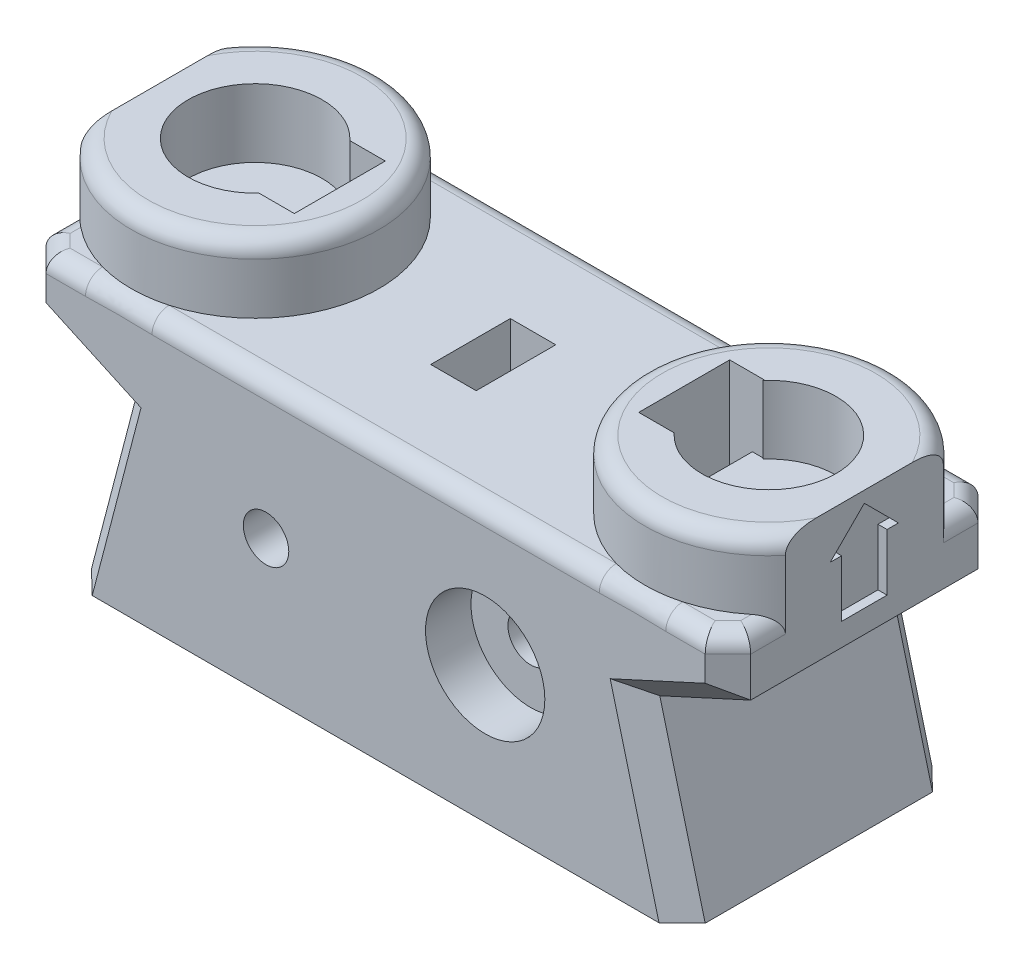
SolidWorks part; units mm, degrees
ref_plane "Front Plane" through (0, 0, 0) normal (0, 0, 1) x (1, 0, 0)
ref_plane "Top Plane" through (0, 0, 0) normal (0, 1, 0) x (1, 0, 0)
ref_plane "Right Plane" through (0, 0, 0) normal (1, 0, 0) x (0, 0, -1)
sketch "Sketch1" plane through (0, 0, 0) normal (0, 0, 1) x (1, 0, 0)
  line L1 (-15.5, 7.5) -> (15.5, 7.5)
  line L2 (-15.5, 7.5) -> (-15.5, -7.5)
  line L3 (-15.5, -7.5) -> (15.5, -7.5)
  line L4 (15.5, 7.5) -> (15.5, -7.5)
  line L5 (-15.5, 7.5) -> (15.5, -7.5) construction
  line L6 (-15.5, -7.5) -> (15.5, 7.5) construction
  point P0 (0, 0)
  dimension "D1" = 31
  dimension "D2" = 15
extrude "Boss-Extrude1" add sketch "Sketch1" along normal mid plane 12
sketch "Sketch2" plane through (0, -7.5, 0) normal (0, -1, 0) x (1, 0, 0)
  line L1 (-10.075, 3.075) -> (10.075, 3.075)
  line L2 (-10.075, 3.075) -> (-10.075, -3.075)
  line L3 (-10.075, -3.075) -> (10.075, -3.075)
  line L4 (10.075, 3.075) -> (10.075, -3.075)
  line L5 (-10.075, 3.075) -> (10.075, -3.075) construction
  line L6 (-10.075, -3.075) -> (10.075, 3.075) construction
  point P0 (0, 0)
  dimension "D1" = 20.15
  dimension "D2" = 6.15
extrude "Cut-Extrude1" cut sketch "Sketch2" against normal blind 13
sketch "Sketch3" plane through (0, 5.5, 0) normal (0, -1, 0) x (1, 0, 0)
  line L0 (8.075, 2.4473) -> (8.075, -2.8954) construction
  line L1 (7.575, 2) -> (8.575, 2)
  line L2 (7.575, 2) -> (7.575, -2)
  line L3 (7.575, -2) -> (8.575, -2)
  line L4 (8.575, 2) -> (8.575, -2)
  line L5 (10.075, -3.075) -> (10.075, 3.075) construction
  line L6 (-19.0138, 0) -> (22.2819, 0) construction
  line L7 (0, 7.5855) -> (0, -7.6677) construction
  line L8 (-8.575, 2) -> (-8.575, -2)
  line L9 (-7.575, -2) -> (-8.575, -2)
  line L10 (-7.575, 2) -> (-7.575, -2)
  line L11 (-7.575, 2) -> (-8.575, 2)
  line L12 (-0.825, 2.2727) -> (-0.825, -2.3089) construction
  line L17 (-10.075, 3.075) -> (-10.075, -3.075) construction
  line L19 (-1.825, 1.75) -> (0.175, 1.75)
  line L20 (-1.825, 1.75) -> (-1.825, -1.75)
  line L21 (-1.825, -1.75) -> (0.175, -1.75)
  line L22 (0.175, 1.75) -> (0.175, -1.75)
  dimension "D1" = 2
  dimension "D2" = 4
  dimension "D3" = 1
  dimension "D4" = 9.25
  dimension "D7" = 2
sketch "Sketch6" plane through (0, 7.5, 0) normal (0, 1, 0) x (1, 0, 0)
  line L0 (15.5, -6) -> (15.5, 6) construction
  line L1 (-15.5, -6) -> (-15.5, 6) construction
  line L2 (-17.2982, 0) -> (18.5048, 0) construction
  circle A0 centre (11.3, 0) radius 2.95
  circle A1 centre (-11.3, 0) radius 2.95
  circle A2 centre (-11.3, 0) radius 5.45
  circle A3 centre (11.3, 0) radius 5.45
  dimension "D1" = 5.9
  dimension "D3" = 5.9
  dimension "D5" = 2.5
  dimension "D6" = 2.5
  dimension "D2" = 4.2
  dimension "D4" = 4.2
extrude "Boss-Extrude3" add sketch "Sketch6" along normal blind 3
extrude "Cut-Extrude3" cut sketch "Sketch3" against normal up to surface (5 mm away) up to face at (-11.3, 10.5, 5.45)
sketch "Sketch7" plane through (0, 10.5, 0) normal (0, 1, 0) x (1, 0, 0)
  line L0 (-8.575, 2) -> (-9.1432, 2)
  line L1 (-9.1432, 2) -> (-9.1432, 0.6994)
  line L2 (-9.1432, 0.6994) -> (-8.575, 0.6994)
  line L3 (-8.575, -1.13) -> (-8.575, 1.13) construction
  line L4 (-8.575, 0.6994) -> (-8.575, 2)
  line L5 (-8.575, -1.13) -> (-8.575, -2)
  line L6 (-8.575, -2) -> (-9.1432, -2)
  line L7 (-9.1432, -2) -> (-9.1432, -0.71)
  line L8 (-9.1432, -0.71) -> (-8.575, -0.71)
  line L9 (-8.575, -0.71) -> (-8.575, -2)
  line L10 (8.575, 1.13) -> (8.575, 2)
  line L11 (8.575, 2) -> (9.0869, 2)
  line L12 (9.0869, 2) -> (9.0869, 1.13)
  line L13 (9.0869, 1.13) -> (8.575, 1.13)
  line L14 (8.575, -2) -> (8.575, -0.592)
  line L15 (8.575, 1.13) -> (8.575, -1.13) construction
  line L16 (8.575, -0.592) -> (9.4303, -0.592)
  line L17 (9.4303, -0.592) -> (9.4303, -2)
  line L18 (9.4303, -2) -> (8.575, -2)
  line M1 (-8.575, 1.13) -> (-8.575, 2)
  line M5 (-8.575, -2) -> (-8.575, -1.13)
  arc M6 (-8.575, -1.13) -> (-8.575, 1.13) centre (-11.3, 0) cw
extrude "Cut-Extrude4" cut sketch "Sketch7" against normal up to surface (3 mm away) contours L2 L4 L0 L1 M6 | L0 M1 M6 | L6 M5 M6 | L9 L8 L7 L6 M6 | L13 L12 L11 L10 | L18 L17 L16 L14 up to face at (11.4125, 7.5, 0)
sketch "Sketch8" plane through (0, -7.5, 0) normal (0, -1, 0) x (1, 0, 0)
  line L4 (-15.5, -6) -> (15.5, -6)
  line L5 (15.5, -6) -> (15.5, 6)
  line L6 (15.5, 6) -> (-15.5, 6)
  line L7 (-15.5, 6) -> (-15.5, -6)
  line L8 (-15.5, -6) -> (15.5, -6)
  line L9 (15.5, -6) -> (15.5, 6)
  line L10 (15.5, 6) -> (-15.5, 6)
  line L11 (-15.5, 6) -> (-15.5, -6)
  dimension "D1" = 0
extrude "Cut-Extrude5" cut sketch "Sketch8" against normal blind 3
sketch "Sketch9" plane through (0, 0, 6) normal (0, 0, 1) x (1, 0, 0)
  line L0 (10.07, -6.4416) -> (10.07, 14.1448) construction
  line L1 (-10.07, 14.1448) -> (-10.07, -6.4416) construction
  line L2 (-15.5, 7.5) -> (-15.5, -4.5) construction
  line L3 (15.5, -4.5) -> (15.5, 7.5) construction
  line L4 (5.82, 4.0391) -> (5.82, 0.7356) construction
  line L5 (-5.82, 4.8454) -> (-5.82, 0.9453) construction
  line L6 (-22.3049, 1.5) -> (21.0526, 1.5) construction
  line L7 (15.5, -4.5) -> (-15.5, -4.5) construction
  circle A0 centre (4.82, 1.5) radius 1
  circle A1 centre (-4.82, 1.5) radius 1
  point P14 (10.07, 3.8516)
  dimension "D3" = 2
  dimension "D4" = 2
  dimension "D1" = 5.43
  dimension "D2" = 5.43
  dimension "D5" = 4.25
  dimension "D6" = 4.25
  dimension "D7" = 6
extrude "Cut-Extrude6" cut sketch "Sketch9" against normal up to surface (12 mm away) up to face at (0, 1.5, -6)
sketch "Sketch10" plane through (0, 0, 6) normal (0, 0, 1) x (1, 0, 0)
  circle A0 centre (4.82, 1.5) radius 2.625
  dimension "D1" = 5.25
extrude "Cut-Extrude7" cut sketch "Sketch10" against normal blind 2
sketch "Sketch11" plane through (0, 0, -6) normal (0, 0, -1) x (-1, 0, 0)
  circle A0 centre (4.82, 1.5) radius 2.625
  dimension "D1" = 5.25
extrude "Cut-Extrude8" cut sketch "Sketch11" against normal blind 2
sketch "Sketch12" plane through (0, -4.5, 0) normal (0, -1, 0) x (1, 0, 0)
  line L0 (15.5, 3.4731) -> (15.5, -3.4731) construction
  line L1 (-15.5, -3.4731) -> (-15.5, 3.4731) construction
  line L2 (15.5, 3.4731) -> (15.5, -3.4731)
  line L3 (-15.5, -3.4731) -> (-15.5, 3.4731)
  arc A0 (15.5, -3.4731) -> (15.5, 3.4731) centre (11.3, 0) ccw construction
  arc A1 (-15.5, 3.4731) -> (-15.5, -3.4731) centre (-11.3, 0) ccw construction
  arc A2 (15.5, -3.4731) -> (15.5, 3.4731) centre (11.3, 0) ccw
  arc A3 (-15.5, 3.4731) -> (-15.5, -3.4731) centre (-11.3, 0) ccw
extrude "Cut-Extrude9" cut sketch "Sketch12" against normal up to surface (15 mm away) up to face at (11.3, 10.5, 5.45)
fillet "Fillet3" radius 0.75 2 edges at (-5.85, 10.5, 0) (5.85, 10.5, 0)
sketch "Sketch13" plane through (0, 0, 6) normal (0, 0, 1) x (1, 0, 0)
  line L0 (-10.07, 12.6901) -> (-10.07, -6.6123) construction
  line L1 (10.07, 12.6901) -> (10.07, -6.6123) construction
  line L2 (-15.5, 7.5) -> (-15.5, -4.5) construction
  line L3 (15.5, -4.5) -> (15.5, 7.5) construction
  line L4 (0, 12.6901) -> (0, -6.6123) construction
  line L5 (13.5, -4.5) -> (11.5, 3.1669)
  line L6 (15.5, -4.5) -> (-15.5, -4.5) construction
  line L7 (11.5, 3.1669) -> (15.5, 5)
  line L8 (-15.5, 5) -> (-15.5, -4.5)
  line L9 (-15.5, -4.5) -> (-13.5, -4.5)
  line L10 (-11.5, 3.1669) -> (-15.5, 5)
  line L11 (-13.5, -4.5) -> (-11.5, 3.1669)
  line L12 (15.5, 5) -> (15.5, -4.5)
  line L13 (15.5, -4.5) -> (13.5, -4.5)
  line L14 (15.5, 7.5) -> (-15.5, 7.5) construction
  dimension "D1" = 5.43
  dimension "D2" = 5.43
  dimension "D3" = 10.07
  dimension "D4" = 10.07
  dimension "D5" = 2
  dimension "D6" = 100
  dimension "D7" = 2.5
  dimension "D8" = 4
extrude "Cut-Extrude10" cut sketch "Sketch13" against normal up to surface (12 mm away) up to face at (-7.445, 1.5, -6)
chamfer "Chamfer2" distance 1 angle 45 12 edges at (12.5, -0.6665, 6) (13.5, 4.0835, 6) (15.5, 6.25, 6) (15.5, 6.25, -6) (13.5, 4.0835, -6) (12.5, -0.6665, -6) (-15.5, 6.25, -6) (-13.5, 4.0835, -6) (-12.5, -0.6665, -6) (-15.5, 6.25, 6) (-13.5, 4.0835, 6) (-12.5, -0.6665, 6)
fillet "Fillet4" radius 0.75 10 edges at (-15.5, 7.5, -4.2366) (-15, 7.5, -5.5) (0, 7.5, -6) (15, 7.5, -5.5) (15.5, 7.5, -4.2366) (15.5, 7.5, 4.2366) (15, 7.5, 5.5) (-15.5, 7.5, 4.2366) (-15, 7.5, 5.5) (0, 7.5, 6)
chamfer "Chamfer3" distance 1.25 angle 45 4 edges at (0, -4.5, 3.075) (-10.075, -4.5, 0) (0, -4.5, -3.075) (10.075, -4.5, 0)
sketch "Sketch14" plane through (15.5, 0, 0) normal (1, 0, 0) x (0, 0, -1)
  line L0 (0, 12.0969) -> (0, -7.2433) construction
  line L1 (-1, 6) -> (1, 6)
  line L2 (1, 6) -> (1, 8.5)
  line L3 (1.5, 8.5) -> (0, 10)
  line L4 (0, 10) -> (-1.5, 8.5)
  line L5 (-1.5, 8.5) -> (-1, 8.5)
  line L6 (-1, 8.5) -> (-1, 6)
  line L7 (1, 8.5) -> (1.5, 8.5)
  line L8 (-8.4785, 7.75) -> (8.2921, 7.75) construction
  line L9 (-2.1095, 10.5) -> (2.1095, 10.5) construction
  line L10 (5, 5) -> (-5, 5) construction
  line L11 (-0.8524, 10) -> (0.9234, 10) construction
  dimension "D1" = 2
  dimension "D2" = 90
  dimension "D3" = 0.5
  dimension "D4" = 0.5
  dimension "D5" = 4
  dimension "D6" = 2.5
  dimension "D7" = 2.5
  dimension "D8" = 2.25
extrude "Cut-Extrude11" cut sketch "Sketch14" against normal blind 0.4
